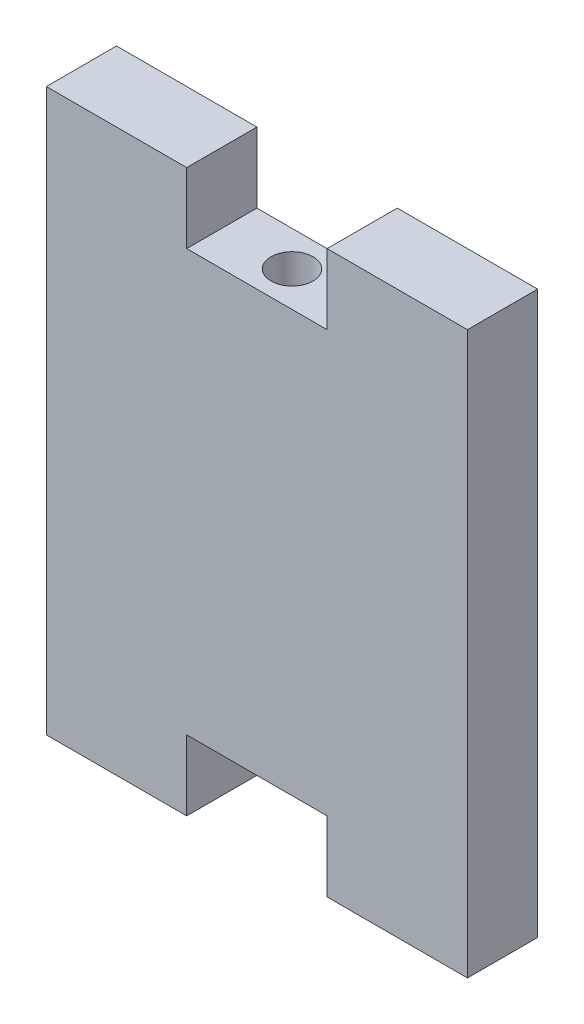
SolidWorks part; units mm, degrees
ref_plane "Front Plane" through (0, 0, 0) normal (0, 0, 1) x (1, 0, 0)
ref_plane "Top Plane" through (0, 0, 0) normal (0, 1, 0) x (1, 0, 0)
ref_plane "Right Plane" through (0, 0, 0) normal (1, 0, 0) x (0, 0, -1)
sketch "Sketch1" plane through (0, 0, 0) normal (0, 0, 1) x (1, 0, 0)
  line L0 (10, 40) -> (30, 40)
  line L1 (-30, -40) -> (-10, -40)
  line L2 (-30, -40) -> (-30, 40)
  line L3 (-30, 40) -> (-10, 40)
  line L4 (30, -40) -> (30, 40)
  line L5 (-30, -40) -> (30, 40) construction
  line L6 (-30, 40) -> (30, -40) construction
  line L8 (-10, 40) -> (-10, 30)
  line L9 (-10, 30) -> (10, 30)
  line L10 (10, 40) -> (10, 30)
  line L11 (0, 0) -> (30, 0) construction
  line L12 (-10, 30) -> (0, 38.227) construction
  line L13 (10, -40) -> (10, -30)
  line L14 (-10, -30) -> (10, -30)
  line L15 (-10, -40) -> (-10, -30)
  line L16 (10, -40) -> (30, -40)
  point P0 (0, 0)
  point P6 (0, 38.227)
  dimension "D1" = 60
  dimension "D2" = 80
  dimension "D3" = 20
  dimension "D4" = 10
extrude "Boss-Extrude1" add sketch "Sketch1" along normal blind 10
sketch "Sketch2" plane through (0, 30, 0) normal (0, 1, 0) x (1, 0, 0)
  line L0 (-10, 0) -> (10, -10) construction
  line L1 (-10, -10) -> (10, 0) construction
  line L4 (10, 0) -> (-10, 0)
  line L5 (-10, 0) -> (-10, -10)
  line L6 (-10, -10) -> (10, -10)
  line L7 (10, -10) -> (10, 0)
  line L8 (10, 0) -> (-10, 0)
  line L9 (-10, 0) -> (-10, -10)
  line L10 (-10, -10) -> (10, -10)
  line L11 (10, -10) -> (10, 0)
  circle A0 centre (0, -5) radius 3
  dimension "D2" = 6
  dimension "D1" = 0
extrude "Cut-Extrude2" cut sketch "Sketch2" against normal through all contours A0
